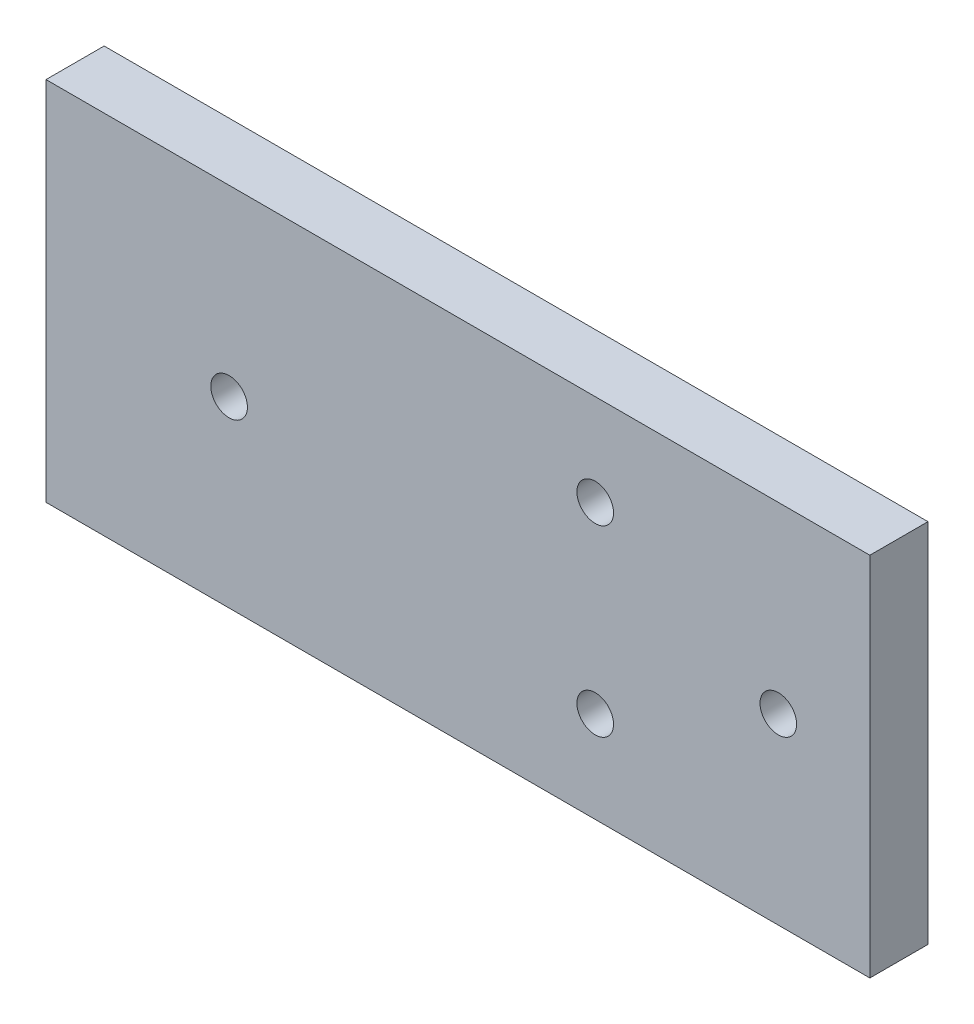
SolidWorks part; units mm, degrees
ref_plane "Front Plane" through (0, 0, 0) normal (0, 0, 1) x (1, 0, 0)
ref_plane "Top Plane" through (0, 0, 0) normal (0, 1, 0) x (1, 0, 0)
ref_plane "Right Plane" through (0, 0, 0) normal (1, 0, 0) x (0, 0, -1)
sketch "Sketch1" plane through (0, 0, 0) normal (0, 0, 1) x (1, 0, 0)
  line L1 (0, 0) -> (90, 0)
  line L2 (0, 0) -> (0, 40)
  line L3 (0, 40) -> (90, 40)
  line L4 (90, 0) -> (90, 40)
  circle A0 centre (60, 30) radius 2
  circle A1 centre (60, 10) radius 2
  circle A4 centre (80, 20) radius 2
  circle A9 centre (20, 20) radius 2
  point P11 (13.3538, 20)
  point P12 (0, 0)
  point P13 (90, 20)
  point P14 (0, 0)
  dimension "D1" = 4
  dimension "D2" = 4
  dimension "D11" = 4
  dimension "D3" = 40
  dimension "D4" = 20
  dimension "D5" = 10
  dimension "D6" = 30
  dimension "D12" = 10
  dimension "D7" = 90
  dimension "D8" = 20
extrude "Boss-Extrude1" add sketch "Sketch1" along normal blind 6.35
equation "\"D11@Sketch1\"=\"D1@Sketch1\""
